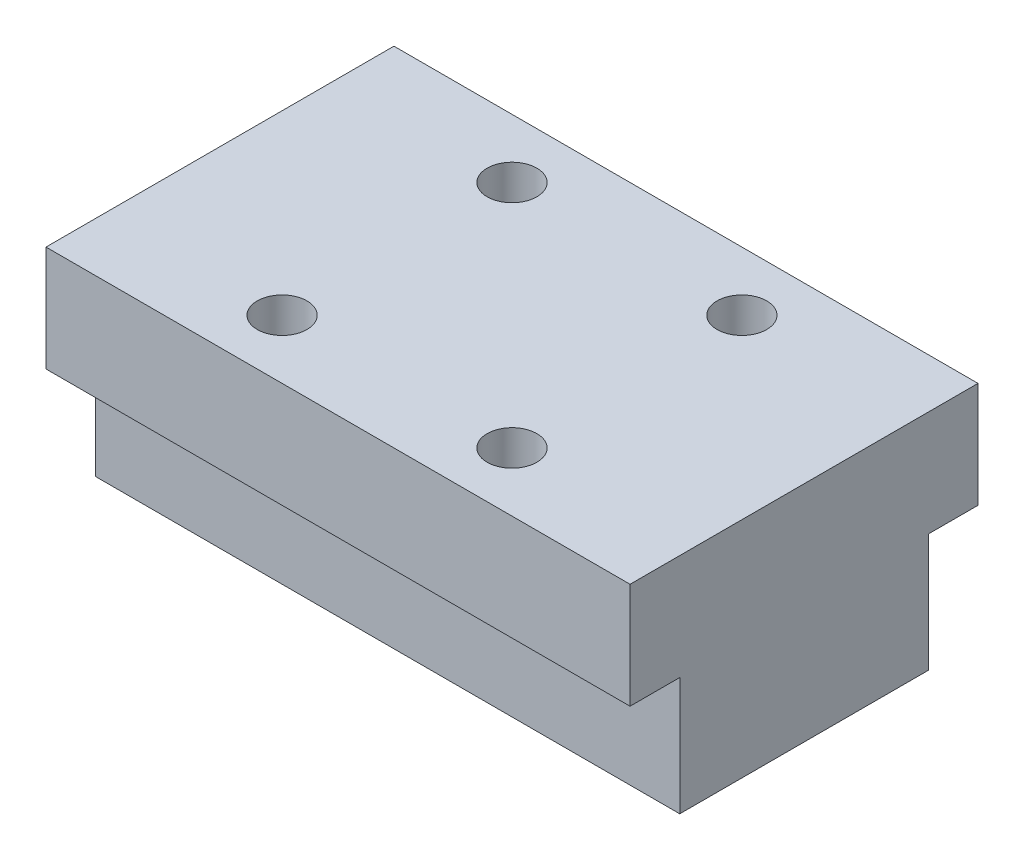
SolidWorks part; units mm, degrees
ref_plane "前视基准面" through (0, 0, 0) normal (0, 0, 1) x (1, 0, 0)
ref_plane "上视基准面" through (0, 0, 0) normal (0, 1, 0) x (1, 0, 0)
ref_plane "右视基准面" through (0, 0, 0) normal (1, 0, 0) x (0, 0, -1)
other "Configuration Table"
sketch "草图1" plane through (0, 0, 0) normal (1, 0, 0) x (0, 0, -1)
  line L1 (-10, -4.75) -> (10, -4.75)
  line L2 (-10, -4.75) -> (-10, 4.75)
  line L3 (-10, 4.75) -> (10, 4.75)
  line L4 (10, -4.75) -> (10, 4.75)
  line L5 (-10, -4.75) -> (10, 4.75) construction
  line L6 (-10, 4.75) -> (10, -4.75) construction
  point P0 (0, 0)
  dimension "D1" = 20
  dimension "D2" = 9.5
extrude "凸台-拉伸1" add sketch "草图1" along normal blind 47
sketch "草图2" plane through (0, 4.75, 0) normal (0, 1, 0) x (1, 0, 0)
  line L0 (0, 14) -> (0, -14)
  line L2 (0, -14) -> (47, -14)
  line L3 (47, -14) -> (47, 14)
  line L4 (47, 14) -> (-0.1961, 14)
  line L5 (47, -10) -> (0, -10) construction
  line M2 (0, 10) -> (0, -10)
  line M3 (0, -10) -> (47, -10)
  line M4 (47, -10) -> (47, 10)
  line M5 (47, 10) -> (0, 10)
  dimension "D1" = 28
  dimension "D2" = 28
  dimension "D3" = 47
  dimension "D4" = 4
extrude "凸台-拉伸2" add sketch "草图2" along normal blind 8.5 contours M5 M2 M3 M4 | L3 L4 L0 M5 | L2 L3 L0 M3
ref_plane "基准面1" through (0, 0, 0) normal (0, 0, -1) x (-1, 0, 0)
ref_plane "基准面2" through (23.5, 0, 0) normal (1, 0, 0) x (0, 0, -1)
sketch "草图3" plane through (0, 13.25, 0) normal (0, 1, 0) x (1, 0, 0)
  line L0 (0, 14) -> (0, -14) construction
  line L1 (47, 14) -> (0, 14) construction
  line L2 (23.5, -9.9) -> (23.5, 9.9) construction
  line L3 (4.675, 0) -> (-4.675, 0) construction
  circle A0 centre (14.25, 9.25) radius 2
  circle A1 centre (32.75, 9.25) radius 2
  circle A2 centre (32.75, -9.25) radius 2
  circle A3 centre (14.25, -9.25) radius 2
  dimension "D1" = 14.25
  dimension "D3" = 4
  dimension "D2" = 4.75
extrude "切除-拉伸1" cut sketch "草图3" against normal blind 8.5
